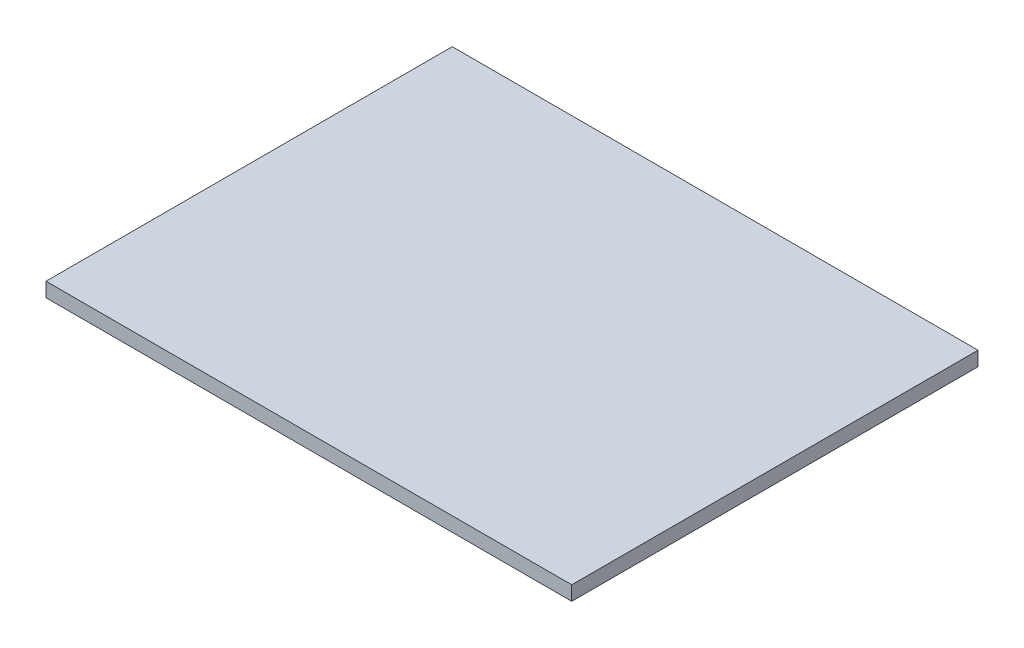
SolidWorks part; units mm, degrees
ref_plane "Front Plane" through (0, 0, 0) normal (0, 0, 1) x (1, 0, 0)
ref_plane "Top Plane" through (0, 0, 0) normal (0, 1, 0) x (1, 0, 0)
ref_plane "Right Plane" through (0, 0, 0) normal (1, 0, 0) x (0, 0, -1)
sketch "Sketch1" plane through (0, 0, 0) normal (0, 1, 0) x (1, 0, 0)
  line L1 (-55, -42.5) -> (55, -42.5)
  line L2 (-55, -42.5) -> (-55, 42.5)
  line L3 (-55, 42.5) -> (55, 42.5)
  line L4 (55, -42.5) -> (55, 42.5)
  line L5 (-55, -42.5) -> (55, 42.5) construction
  line L6 (-55, 42.5) -> (55, -42.5) construction
  point P0 (0, 0)
  dimension "D1" = 85
  dimension "D2" = 110
extrude "Boss-Extrude1" add sketch "Sketch1" along normal blind 3
